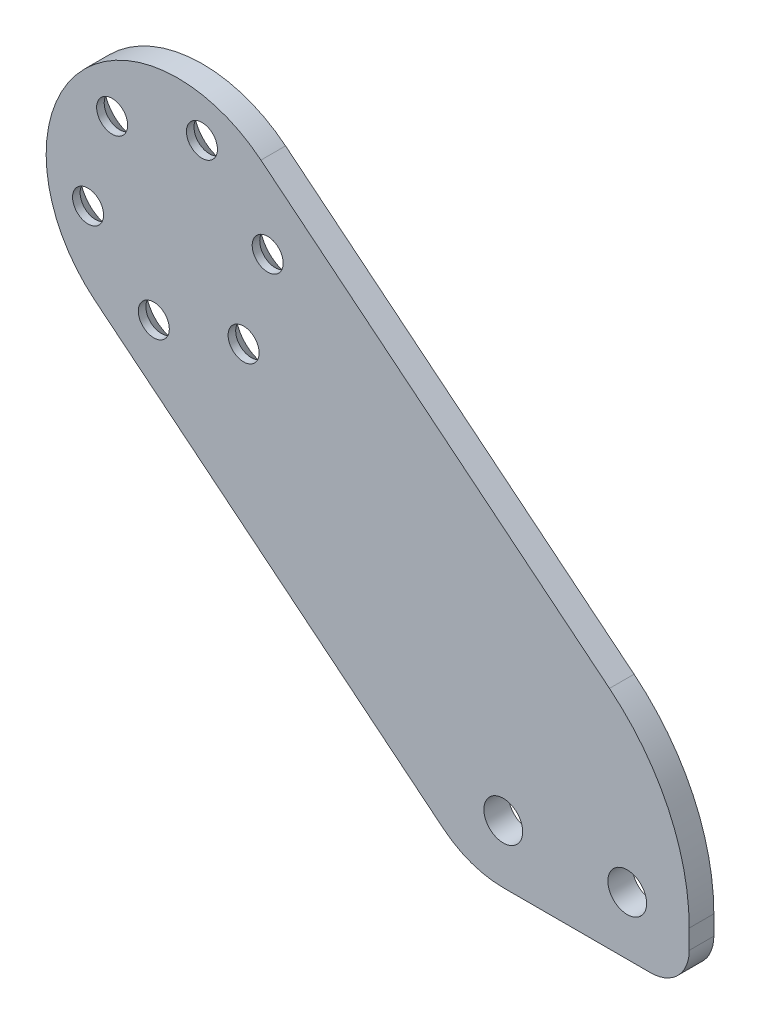
SolidWorks part; units mm, degrees
ref_plane "Front Plane" through (0, 0, 0) normal (0, 0, 1) x (1, 0, 0)
ref_plane "Top Plane" through (0, 0, 0) normal (0, 1, 0) x (1, 0, 0)
ref_plane "Right Plane" through (0, 0, 0) normal (1, 0, 0) x (0, 0, -1)
sketch "Sketch1" plane through (0, 0, 0) normal (0, 0, 1) x (1, 0, 0)
  line L0 (34.2613, -49.7518) -> (-10.7219, -13.1924)
  line L5 (-8.4853, 8.4853) -> (0, 0) construction
  line L6 (0, -12) -> (0, 12) construction
  line L8 (55.7052, -23.367) -> (10.7219, 13.1924)
  line L9 (42, -45) -> (58, -45) construction
  line L10 (42, -45) -> (42, -52.5) construction
  line L14 (66, -45) -> (66, -52.5)
  line L16 (42, -52.5) -> (66, -52.5)
  line L17 (34, -37.5) -> (34, -52.5) construction
  line L18 (34, -52.5) -> (42, -52.5) construction
  line L19 (66, -37.5) -> (66, -45) construction
  line L20 (66, -37.5) -> (34, -37.5) construction
  line L21 (66, -45) -> (58, -45) construction
  line L22 (34.2613, -49.7518) -> (55.7052, -23.367) construction
  line L23 (50, -37.5) -> (50, -52.5) construction
  arc A0 (10.7219, 13.1924) -> (-10.7219, -13.1924) centre (0, 0) ccw
  circle A3 centre (-8.4853, 8.4853) radius 2
  circle A5 centre (3.1058, 11.5911) radius 2
  circle A6 centre (11.5911, 3.1058) radius 2
  circle A7 centre (8.4853, -8.4853) radius 2
  circle A10 centre (0, 0) radius 12 construction
  circle A11 centre (42, -45) radius 2.5
  circle A12 centre (58, -45) radius 2.5
  circle A14 centre (-3.1058, -11.5911) radius 2
  circle A15 centre (-11.5911, -3.1058) radius 2
  circle A16 centre (0, 0) radius 50 construction
  arc A17 (34.2613, -49.7518) -> (42, -52.5) centre (42, -40.2301) ccw
  arc A18 (55.7052, -23.367) -> (66, -45) centre (38.1233, -45) cw
  point P4 (50, -45)
  point P30 (0, 0)
  point P35 (0, 0)
  dimension "D2" = 34
  dimension "D4" = 4
  dimension "D5" = 50
  dimension "D8" = 32
  dimension "D7" = 5
  dimension "D3" = 24
  dimension "D12" = 100
  dimension "D1" = 45
  dimension "D10" = 16
  dimension "D13" = 45
  dimension "D15" = 15
  dimension "D6" = 6
extrude "Boss-Extrude1" add sketch "Sketch1" along normal blind 3.175
fillet "Fillet1" radius 5 1 edges at (66, -52.5, 1.5875)
chamfer "Chamfer1" distance 2.2 angle 45 6 edges at (10.4853, -8.4853, 0) (-1.1058, -11.5911, 0) (-9.5911, -3.1058, 0) (-6.4853, 8.4853, 0) (5.1058, 11.5911, 0) (13.5911, 3.1058, 0)
